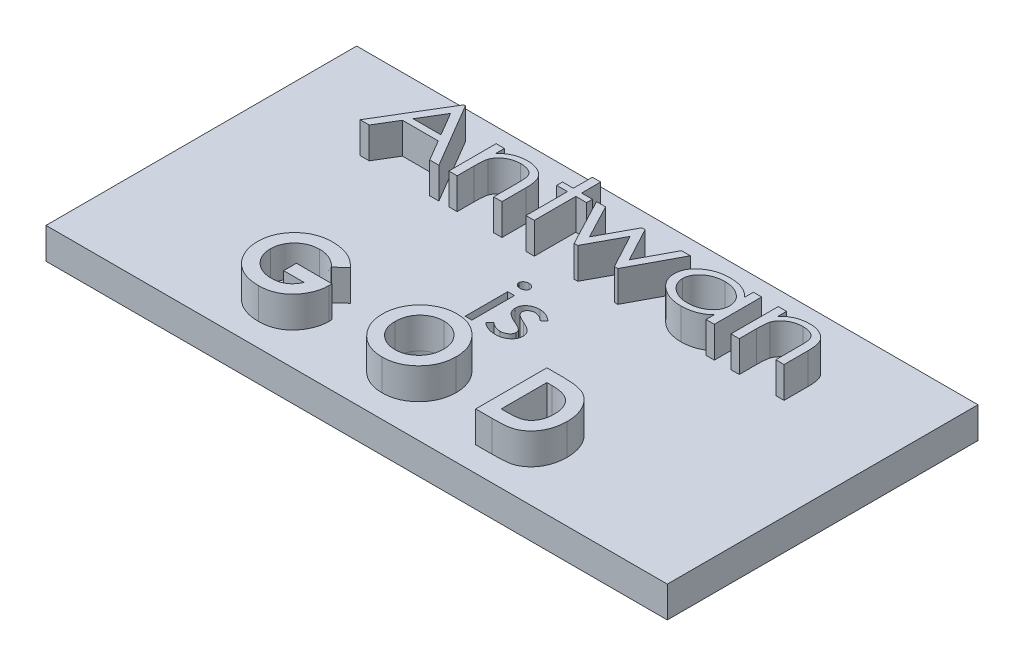
SolidWorks part; units mm, degrees
ref_plane "Front Plane" through (0, 0, 0) normal (0, 0, 1) x (1, 0, 0)
ref_plane "Top Plane" through (0, 0, 0) normal (0, 1, 0) x (1, 0, 0)
ref_plane "Right Plane" through (0, 0, 0) normal (1, 0, 0) x (0, 0, -1)
sketch "Sketch1" plane through (0, 0, 0) normal (0, 1, 0) x (1, 0, 0)
  line L0 (-25.4, 0) -> (25.4, 0) construction
  line L1 (-25.4, -12.7) -> (25.4, -12.7)
  line L2 (-25.4, -12.7) -> (-25.4, 12.7)
  line L3 (-25.4, 12.7) -> (25.4, 12.7)
  line L4 (25.4, -12.7) -> (25.4, 12.7)
  line L5 (-25.4, -12.7) -> (25.4, 12.7) construction
  line L6 (-25.4, 12.7) -> (25.4, -12.7) construction
  point P0 (0, 0)
  dimension "D1" = 50.8
  dimension "D2" = 25.4
extrude "Boss-Extrude1" add sketch "Sketch1" along normal blind 2.54 contours L2 L1 L4 L3
sketch "Sketch2" plane through (0, 2.54, 0) normal (0, 1, 0) x (1, 0, 0)
  line L0 (-25.4, 5.08) -> (25.4, 5.08) construction
  line L1 (-25.4, -12.7) -> (-25.4, 12.7) construction
  line L2 (25.4, -12.7) -> (25.4, 12.7) construction
  line L3 (-25.4, 12.7) -> (25.4, 12.7) construction
  text T0 "Antwan" font "Century Gothic" height in points 20
  dimension "D1" = 7.62
extrude "Boss-Extrude2" add sketch "Sketch2" along normal blind 2.54
sketch "Sketch3" plane through (0, 2.54, 0) normal (0, 1, 0) x (1, 0, 0)
  line L0 (-25.4, -1.9981) -> (25.4, -1.9981) construction
  line L3 (-25.4, 12.7) -> (25.4, 12.7) construction
  text T0 "is" font "Century Gothic" height in points 18
  dimension "D1" = 14.6981
extrude "Cut-Extrude1" cut sketch "Sketch3" against normal blind 5.08
sketch "Sketch4" plane through (0, 2.54, 0) normal (0, 1, 0) x (1, 0, 0)
  line L0 (-25.4, -10.668) -> (25.4, -10.668) construction
  line L1 (-25.4, -12.7) -> (-25.4, 12.7) construction
  line L2 (25.4, -12.7) -> (25.4, 12.7) construction
  line L3 (-25.4, -12.7) -> (25.4, -12.7) construction
  text T0 "<b>GOD</b>" font "Century Gothic" height in points 22
  dimension "D1" = 2.032
extrude "Boss-Extrude3" add sketch "Sketch4" along normal blind 2.54
sketch "Sketch5" plane through (0, 2.54, 0) normal (0, 1, 0) x (1, 0, 0)
  circle A0 centre (0.1604, -7.7477) radius 2.0034
  spline S0 degree 3 poles (0.1819, -5.7427) (0.1138, -5.7445) (-0.0206, -5.7481) (-0.2178, -5.7756) (-0.4071, -5.8195) (-0.5874, -5.883) (-0.7597, -5.964) (-0.924, -6.0619) (-1.0783, -6.1803) (-1.2245, -6.3128) (-1.3565, -6.4603) (-1.4732, -6.6185) (-1.5709, -6.787) (-1.6526, -6.9642) (-1.7142, -7.1522) (-1.758, -7.3494) (-1.7857, -7.5562) (-1.7892, -7.6972) (-1.791, -7.7692) knots 0 0 0 0 0.064609 0.127512 0.188521 0.248708 0.308598 0.368812 0.429888 0.492802 0.555743 0.617485 0.678969 0.740198 0.80236 0.866245 0.931707 1 1 1 1 construction
  spline S1 degree 3 poles (0.2029, -9.7725) (0.2698, -9.7706) (0.4015, -9.767) (0.595, -9.7399) (0.7804, -9.6939) (0.9588, -9.6309) (1.1297, -9.549) (1.2923, -9.448) (1.4469, -9.3292) (1.5929, -9.195) (1.7264, -9.0468) (1.8428, -8.8878) (1.9436, -8.7215) (2.0236, -8.5454) (2.0876, -8.3614) (2.1309, -8.1685) (2.1589, -7.9675) (2.1624, -7.8308) (2.1642, -7.7611) knots 0 0 0 0 0.064147 0.126212 0.186841 0.246936 0.307256 0.368151 0.430071 0.493875 0.557981 0.62087 0.682525 0.744036 0.805889 0.868968 0.933247 1 1 1 1 construction
extrude "Cut-Extrude2" cut sketch "Sketch5" against normal blind 5.08 contours A0
